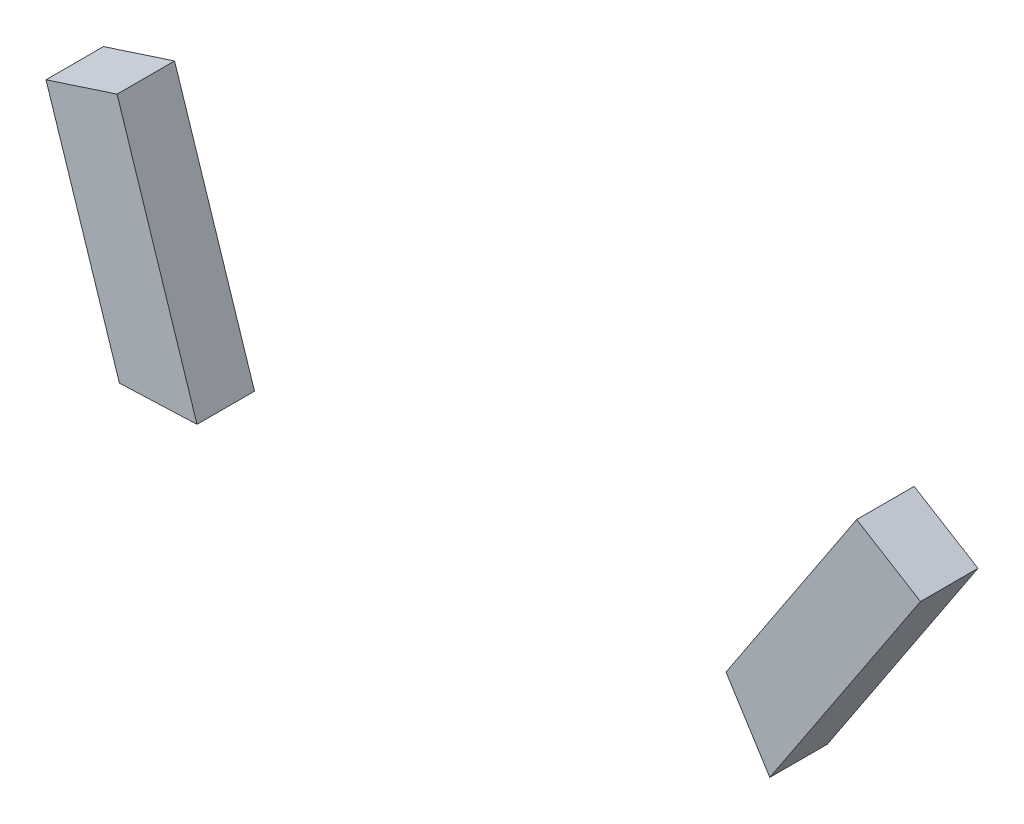
SolidWorks part; units mm, degrees
ref_plane "Front Plane" through (0, 0, 0) normal (0, 0, 1) x (1, 0, 0)
ref_plane "Top Plane" through (0, 0, 0) normal (0, 1, 0) x (1, 0, 0)
ref_plane "Right Plane" through (0, 0, 0) normal (1, 0, 0) x (0, 0, -1)
sketch "Sketch1" plane through (0, 0, 0) normal (0, 0, 1) x (1, 0, 0)
  line L0 (0, -21.2809) -> (0, 20.8576) construction
  line L1 (-23.4901, 0) -> (24.9244, 0) construction
  line L2 (0, 0) -> (5.5969, 9.6942) construction
  line L3 (0, 0) -> (-5.6466, 9.7801) construction
  line L4 (2.05, 3.5507) -> (-1.6508, 5.6874) construction
  line L5 (-2.05, 3.5507) -> (1.6508, 5.6874) construction
  line L6 (0.8318, 0.175) -> (2.7945, 0.175)
  line L7 (0.8318, -0.175) -> (2.7945, -0.175)
  line L8 (-0.175, 0.8318) -> (-0.175, 2.7945)
  line L9 (0.175, 0.8318) -> (0.175, 2.7945)
  line L10 (0.175, -0.8318) -> (0.175, -2.7945)
  line L11 (-0.175, -0.8318) -> (-0.175, -2.7945)
  line L12 (-0.8318, -0.175) -> (-2.7945, -0.175)
  line L13 (-0.8318, 0.175) -> (-2.7945, 0.175)
  line L14 (0, 0) -> (6.6911, 7.6973) construction
  line L15 (0, 0) -> (-6.6911, 7.6973) construction
  line L16 (0, 4.7343) -> (6.5895, 2.1386) construction
  line L17 (2.6898, 3.0943) -> (2.2024, 3.8667)
  line L18 (0, 0) -> (2.5071, 3.384) construction
  line L19 (2.5071, 3.384) -> (2.4713, 3.3358)
  line L20 (2.6898, 3.0943) -> (1.7172, 2.6408)
  line L21 (3.6667, 2.0717) -> (3.6145, 2.0422)
  line L22 (3.7159, 1.7327) -> (3.5847, 2.6366)
  line L23 (3.7159, 1.7327) -> (2.6429, 1.714)
  line L24 (4.1923, 0.4012) -> (4.1326, 0.3955)
  line L25 (4.0994, 0.0716) -> (4.3472, 0.9506)
  line L26 (4.0994, 0.0716) -> (3.1115, 0.4909)
  line L27 (3.9931, -1.3387) -> (3.9362, -1.3196)
  line L28 (3.7741, -1.602) -> (4.3581, -0.8998)
  line L29 (3.7741, -1.602) -> (3.0422, -0.8171)
  line L30 (3.1034, -2.847) -> (3.0592, -2.8065)
  line L31 (2.7962, -2.9986) -> (3.6153, -2.5945)
  line L32 (2.7962, -2.9986) -> (2.4468, -1.9838)
  line L33 (1.6771, -3.8632) -> (1.6532, -3.8081)
  line L34 (1.3348, -3.8766) -> (2.2475, -3.8407)
  line L35 (1.3348, -3.8766) -> (1.4284, -2.8075)
  line L36 (-0.0392, -4.2113) -> (-0.0387, -4.1513)
  line L37 (-0.3573, -4.0844) -> (0.491, -4.4228)
  line L38 (-0.3573, -4.0844) -> (0.1629, -3.1458)
  line L39 (-1.7487, -3.8313) -> (-1.7238, -3.7767)
  line L40 (-1.9877, -3.5859) -> (-1.3504, -4.2401)
  line L41 (-1.9877, -3.5859) -> (-1.1306, -2.9401)
  line L42 (-3.1558, -2.7888) -> (-3.1109, -2.749)
  line L43 (-3.2744, -2.4674) -> (-2.9582, -3.3243)
  line L44 (-3.2744, -2.4674) -> (-2.2287, -2.226)
  line L45 (-4.0173, -1.2641) -> (-3.9601, -1.2461)
  line L46 (-3.9949, -0.9223) -> (-4.0546, -1.8337)
  line L47 (-3.9949, -0.9223) -> (-2.9415, -1.1271)
  line L48 (-4.1841, 0.4792) -> (-4.1245, 0.4724)
  line L49 (-4.0247, 0.7823) -> (-4.4499, -0.026)
  line L50 (-4.0247, 0.7823) -> (-3.1456, 0.1668)
  line L51 (-3.6275, 2.1396) -> (-3.5758, 2.1091)
  line L52 (-3.3585, 2.3517) -> (-4.0757, 1.7862)
  line L53 (-3.3585, 2.3517) -> (-2.8058, 1.4318)
  line L54 (-2.4436, 3.4301) -> (-2.4088, 3.3812)
  line L55 (-2.1117, 3.5144) -> (-2.9969, 3.2895)
  line L56 (-2.1117, 3.5144) -> (-1.9809, 2.4492)
  line L57 (-0.8372, 4.1274) -> (-0.8253, 4.0686)
  line L58 (-0.4997, 4.0694) -> (-1.3998, 4.2241)
  line L59 (-0.4997, 4.0694) -> (-0.8134, 3.0432)
  line L60 (0.9139, 4.1111) -> (0.9009, 4.0525)
  line L61 (1.1987, 3.9208) -> (0.4393, 4.4282)
  line L62 (1.1987, 3.9208) -> (0.4947, 3.1109)
  line L63 (0, 4.7343) -> (-2.5531, 3.1697) construction
  line L64 (-2.05, 3.5507) -> (-2.4328, 4.7289) construction
  line L65 (-2.0183, 3.4974) -> (-2.5292, 5.0699)
  line L66 (2.5071, 4.3424) -> (3.1715, 5.3462) construction
  line L67 (2.2024, 3.8667) -> (3.1115, 5.2402)
  line L68 (2.5071, 3.384) -> (3.5557, 4.9683)
  line L69 (3.5557, 4.9683) -> (3.1115, 5.2402)
  line L70 (-2.5292, 5.0699) -> (-2.0347, 5.2306)
  line L71 (-2.0347, 5.2306) -> (-1.4785, 3.5187)
  line L72 (-2.1117, 3.5144) -> (-1.2626, 3.7301) construction
  line L73 (-2.0183, 3.4974) -> (-1.4785, 3.5187)
  line L74 (0, 4.7343) -> (-0.7323, 13.1045) construction
  line L75 (3.1336, 5.4612) -> (3.7485, 5.0848)
  line L76 (3.7797, 4.9444) -> (3.2146, 4.0906)
  line L77 (2.998, 5.4311) -> (2.9748, 5.396)
  line L78 (0.067, 6.2631) -> (0.1001, 5.8849)
  line L79 (3.2146, 4.0906) -> (2.93, 3.9142)
  line L80 (2.93, 3.9142) -> (2.88, 3.9474)
  line L81 (-2.6861, 5.2292) -> (-2.0014, 5.4517)
  line L82 (-1.8754, 5.3875) -> (-1.7926, 5.1326)
  line L83 (-2.7504, 5.1032) -> (-2.4797, 4.2702)
  line L84 (-2.4797, 4.2702) -> (-2.2599, 4.0467)
  line L85 (-2.2599, 4.0467) -> (-2.2028, 4.0652)
  line L86 (-0.3315, 6.2283) -> (-0.2984, 5.85)
  line L87 (0.067, 6.2631) -> (-0.31, 10.5723)
  line L88 (-0.3315, 6.2283) -> (-0.7085, 10.5374)
  line L89 (0, 4.7343) -> (-1.8171, 12.9313) construction
  line L90 (0, 13.1343) -> (-1.0909, 9.5661) construction
  line L91 (-0.2672, 11.2304) -> (-0.2957, 11.5563)
  line L92 (-0.8649, 11.1781) -> (-0.8934, 11.504)
  line L93 (-0.8649, 11.1781) -> (-0.2672, 11.2304)
  line L94 (-0.5939, 10.5474) -> (-0.4246, 10.5622)
  line L95 (-0.4246, 10.5622) -> (-0.5425, 11.9099)
  line L96 (-0.5425, 11.9099) -> (-0.64, 12.0491)
  line L97 (-0.5939, 10.5474) -> (-0.7118, 11.895)
  line L98 (-0.7118, 11.895) -> (-0.64, 12.0491)
  line L99 (-0.3654, 10.9187) -> (-0.3218, 10.4206)
  line L100 (-0.3218, 10.4206) -> (-0.6705, 10.3901)
  line L101 (-0.6705, 10.3901) -> (-0.7141, 10.8882)
  line L102 (-0.7141, 10.8882) -> (-0.3654, 10.9187)
  circle A0 centre (0, 0) radius 4.1
  circle A1 centre (0, 4.7343) radius 0.25
  circle A2 centre (0, 0) radius 0.35
  arc A3 (-0.175, 0.8318) -> (-0.8318, 0.175) centre (0, 0) ccw
  arc A4 (-0.175, 2.7945) -> (-2.7945, 0.175) centre (0, 0) ccw
  arc A5 (0.6577, 3.0806) -> (0.4947, 3.1109) centre (0, 0) ccw
  arc A6 (-0.8318, -0.175) -> (-0.175, -0.8318) centre (0, 0) ccw
  arc A7 (0.8318, 0.175) -> (0.175, 0.8318) centre (0, 0) ccw
  arc A8 (0.175, -0.8318) -> (0.8318, -0.175) centre (0, 0) ccw
  arc A9 (-2.7945, -0.175) -> (-0.175, -2.7945) centre (0, 0) ccw
  arc A10 (2.7945, 0.175) -> (0.175, 2.7945) centre (0, 0) ccw
  arc A11 (0.175, -2.7945) -> (2.7945, -0.175) centre (0, 0) ccw
  arc A12 (2.05, 3.5507) -> (1.8799, 6.1728) centre (0, 4.7343) ccw
  circle A13 centre (0, 0) radius 4.2115
  arc A14 (2.4713, 3.3358) -> (2.4182, 3.0865) centre (2.388, 3.2233) cw
  arc A15 (0.6577, 3.0806) -> (2.4182, 3.0865) centre (1.5242, 7.1391) ccw
  arc A16 (1.8538, 2.5467) -> (3.4645, 1.8361) centre (4.2961, 5.902) ccw
  arc A17 (2.7628, 3.1783) -> (2.7631, 3.1784) centre (1.5242, 7.1391) ccw
  arc A18 (3.6145, 2.0422) -> (3.4645, 1.8361) centre (3.4926, 1.9733) cw
  arc A19 (2.7294, 1.5725) -> (3.9118, 0.2683) centre (6.3253, 3.6443) ccw
  arc A20 (4.1326, 0.3955) -> (3.9118, 0.2683) centre (3.9932, 0.3821) cw
  arc A21 (3.133, 0.3264) -> (3.6827, -1.346) centre (7.2607, 0.7565) ccw
  arc A22 (3.9362, -1.3196) -> (3.6827, -1.346) centre (3.8034, -1.2751) cw
  arc A23 (2.995, -0.9761) -> (2.8169, -2.7275) centre (6.9407, -2.2621) ccw
  arc A24 (3.0592, -2.8065) -> (2.8169, -2.7275) centre (2.956, -2.7118) cw
  arc A25 (2.339, -2.1099) -> (1.4639, -3.6375) centre (5.4206, -4.8895) ccw
  arc A26 (1.6532, -3.8081) -> (1.4639, -3.6375) centre (1.5974, -3.6797) cw
  arc A27 (1.2786, -2.8788) -> (-0.1421, -3.9184) centre (2.9632, -6.6715) ccw
  arc A28 (-0.0387, -4.1513) -> (-0.1421, -3.9184) centre (-0.0374, -4.0113) cw
  arc A29 (-0.0028, -3.15) -> (-1.7236, -3.5219) centre (-0.0066, -7.3) ccw
  arc A30 (-1.7238, -3.7767) -> (-1.7236, -3.5219) centre (-1.6657, -3.6493) cw
  arc A31 (-1.2838, -2.8765) -> (-3.007, -2.5163) centre (-2.9752, -6.6662) ccw
  arc A32 (-3.1109, -2.749) -> (-3.007, -2.5163) centre (-3.006, -2.6563) cw
  arc A33 (-2.3428, -2.1057) -> (-3.7706, -1.0757) centre (-5.4293, -4.8798) ccw
  arc A34 (-3.9601, -1.2461) -> (-3.7706, -1.0757) centre (-3.8265, -1.204) cw
  arc A35 (-2.9967, -0.9707) -> (-3.8821, 0.5509) centre (-6.9447, -2.2496) ccw
  arc A36 (-4.1245, 0.4724) -> (-3.8821, 0.5509) centre (-3.9854, 0.4564) cw
  arc A37 (-3.1324, 0.3321) -> (-3.3224, 2.0823) centre (-7.2593, 0.7696) ccw
  arc A38 (-3.5758, 2.1091) -> (-3.3224, 2.0823) centre (-3.4552, 2.038) cw
  arc A39 (-2.7266, 1.5775) -> (-2.1882, 3.2536) centre (-6.3187, 3.6557) ccw
  arc A40 (-2.4088, 3.3812) -> (-2.1882, 3.2536) centre (-2.3276, 3.2672) cw
  arc A41 (-1.8492, 2.5501) -> (-0.6757, 3.8623) centre (-4.2855, 5.9097) ccw
  arc A42 (-0.8253, 4.0686) -> (-0.6757, 3.8623) centre (-0.7975, 3.9314) cw
  arc A43 (-0.6522, 3.0818) -> (0.9537, 3.8033) centre (-1.5113, 7.1418) ccw
  arc A44 (0.9009, 4.0525) -> (0.9537, 3.8033) centre (0.8705, 3.9159) cw
  arc A45 (2.0666, 2.3773) -> (1.575, 2.728) centre (0, 0) ccw
  arc A46 (2.7294, 1.5725) -> (2.6429, 1.714) centre (0, 0) ccw
  arc A47 (3.133, 0.3264) -> (3.1115, 0.4909) centre (0, 0) ccw
  arc A48 (2.995, -0.9761) -> (3.0422, -0.8171) centre (0, 0) ccw
  arc A49 (2.339, -2.1099) -> (2.4468, -1.9838) centre (0, 0) ccw
  arc A50 (-0.6522, 3.0818) -> (-0.8134, 3.0432) centre (0, 0) ccw
  arc A51 (-1.575, 2.728) -> (-2.0666, 2.3773) centre (0, 0) ccw
  arc A52 (-2.7266, 1.5775) -> (-2.8058, 1.4318) centre (0, 0) ccw
  arc A53 (-3.1324, 0.3321) -> (-3.1456, 0.1668) centre (0, 0) ccw
  arc A54 (-2.9967, -0.9707) -> (-2.9415, -1.1271) centre (0, 0) ccw
  arc A55 (-2.3428, -2.1057) -> (-2.2287, -2.226) centre (0, 0) ccw
  arc A56 (-1.2838, -2.8765) -> (-1.1306, -2.9401) centre (0, 0) ccw
  arc A57 (-0.0028, -3.15) -> (0.1629, -3.1458) centre (0, 0) ccw
  arc A58 (1.2786, -2.8788) -> (1.4284, -2.8075) centre (0, 0) ccw
  arc A59 (-2.05, 3.5507) -> (-0.5036, 2.4213) centre (0, 4.7343) ccw
  arc A60 (1.0177, 5.1638) -> (2.0583, 5.0774) centre (1.3569, 2.9395) cw
  arc A61 (0.2412, 4.4152) -> (2.5336, 4.367) centre (1.3569, 2.9395) cw
  arc A62 (-0.2238, 4.4028) -> (-1.7102, 4.232) centre (-0.8673, 3.4497) ccw
  arc A63 (3.7485, 5.0848) -> (3.7797, 4.9444) centre (3.6963, 4.9996) cw
  arc A64 (2.998, 5.4311) -> (3.1336, 5.4612) centre (3.0814, 5.3759) cw
  arc A65 (-0.2238, 4.4028) -> (0.2412, 4.4152) centre (0, 4.7343) ccw
  arc A66 (2.9748, 5.396) -> (2.0583, 5.0774) centre (2.3077, 5.8375) cw
  arc A67 (1.0177, 5.1638) -> (0.1001, 5.8849) centre (0.8971, 5.9546) cw
  arc A68 (-1.8754, 5.3875) -> (-2.0014, 5.4517) centre (-1.9705, 5.3566) ccw
  arc A69 (-2.7504, 5.1032) -> (-2.6861, 5.2292) centre (-2.6552, 5.1341) cw
  arc A70 (-0.2984, 5.85) -> (-0.754, 5.1723) centre (-0.9459, 5.7934) cw
  arc A71 (-1.7926, 5.1326) -> (-1.5095, 5.0037) centre (-1.5211, 5.3535) ccw
  arc A72 (-0.31, 10.5723) -> (-0.0079, 11.1276) centre (0.2577, 10.6233) cw
  arc A73 (-0.0652, 5.4791) -> (0, 5.5041) centre (-2.8729, 12.8867) ccw
  arc A74 (-1.5095, 5.0037) -> (-0.754, 5.1723) centre (-2.8729, 12.8867) ccw
  arc A75 (-0.0079, 11.1276) -> (0.0594, 11.5321) centre (0.4209, 11.2641) cw
  arc A76 (0.0594, 11.5321) -> (0.2329, 11.9395) centre (-0.7039, 12.0977) ccw
  arc A77 (-0.3152, 11.3278) -> (-0.8812, 11.5261) centre (-0.5952, 11.4355) ccw
  circle A78 centre (0, 13.1343) radius 1.2
  circle A79 centre (0, 13.1343) radius 2
  arc A80 (-0.7085, 10.5374) -> (-1.1024, 11.0318) centre (-1.2764, 10.489) ccw
  arc A81 (-1.1024, 11.0318) -> (-1.2389, 11.4185) centre (-1.5484, 11.0918) ccw
  arc A82 (-1.2389, 11.4185) -> (-1.4805, 11.7896) centre (-0.5855, 12.1081) cw
  arc A83 (-1.4805, 11.7896) -> (-0.8934, 11.504) centre (-0.6802, 12.6886) ccw
  arc A84 (0.2329, 11.9395) -> (-0.2957, 11.5563) centre (-0.7114, 12.6858) cw
  circle A85 centre (0, 13.1343) radius 1.8
  arc A86 (-0.8715, 11.5024) -> (-0.3375, 11.3153) centre (0, 13.1343) ccw
  arc A87 (-0.3375, 11.3153) -> (-0.3152, 11.3278) centre (-0.3338, 11.335) ccw
  circle A88 centre (0, 13.1343) radius 1.85 construction
  arc A89 (-0.8789, 11.3381) -> (-0.8787, 11.3377) centre (-0.5952, 11.4355) ccw
  arc A90 (-0.8715, 11.5024) -> (-0.8812, 11.5261) centre (-0.8621, 11.5201) cw
  circle A91 centre (0, 13.1343) radius 0.4
  point P36 (0, 0)
  point P40 (2.5071, 3.384)
  point P180 (0, 0)
  point P182 (-2.0183, 3.4974)
  point P245 (0, 13.1343)
  point P252 (-0.5661, 11.2043)
  point P268 (-0.5661, 11.2043)
  point P273 (-0.5092, 10.5548)
  point P276 (1.85, 13.1343)
  dimension "D1" = 8.2
  dimension "D4" = 0.5
  dimension "D5" = 0.7
  dimension "D6" = 1.7
  dimension "D7" = 5.6
  dimension "D8" = 6.3
  dimension "D17" = 0.14
  dimension "D18" = 8.3
  dimension "D28" = 0.4
  dimension "D29" = 1.85
  dimension "D31" = 1.15
  dimension "D34" = 2.25
  dimension "D37" = 0.1
  dimension "D39" = 0.1
  dimension "D40" = 0.8
  dimension "D41" = 0.8
  dimension "D46" = 0.1
  dimension "D48" = 0.1
  dimension "D52" = 0.35
  dimension "D53" = 0.65
  dimension "D54" = 0.2
  dimension "D55" = 0.95
  dimension "D56" = 0.45
  dimension "D57" = 0.57
  dimension "D58" = 0.2375
  dimension "D61" = 0.6
  dimension "D62" = 2.4
  dimension "D64" = 4
  dimension "D65" = 3.6
  dimension "D70" = 0.05
  dimension "D71" = 0.02
  dimension "D76" = 0.8
  dimension "D2" = 60
  dimension "D3" = 30
  dimension "D9" = 0.35
  dimension "D11" = 11
  dimension "D12" = 8.5
  dimension "D13" = 0.9133
  dimension "D14" = 0.3425
  dimension "D15" = 0.06
  dimension "D16" = 24
  dimension "D20" = 1.5
  dimension "D21" = 12
  dimension "D22" = 1.8
  dimension "D23" = 3.5
  dimension "D24" = 1.6471
  dimension "D25" = 1.9
  dimension "D26" = 0.52
  dimension "D27" = 12
  dimension "D30" = 0.6
  dimension "D32" = 0.75
  dimension "D33" = 5
  dimension "D35" = 0.2
  dimension "D36" = 0.2
  dimension "D38" = 0.2
  dimension "D42" = 0.06
  dimension "D43" = 1
  dimension "D44" = 0.2
  dimension "D45" = 0.2
  dimension "D47" = 0.2
  dimension "D49" = 0.9
  dimension "D50" = 0.6
  dimension "D51" = 0.06
  dimension "D59" = 1.93
  dimension "D60" = 8.4
  dimension "D63" = 17
  dimension "D66" = 0.17
  dimension "D67" = 1.5
  dimension "D68" = 30
  dimension "D69" = 0.6
  dimension "D72" = 0.35
  dimension "D73" = 0.175
  dimension "D74" = 0.5
  dimension "D75" = 0.15
  dimension "D10" = 4
  dimension "D19" = 15
extrude "Boss-Extrude1" add sketch "Sketch1" along normal blind 0.4 contours L68 L69 L67 L17 | A13 L71 L70 L65 | L71 A13 L65 A0 | L71 A0 L65 L73
equation "\"D14@Sketch1\"=\"D13@Sketch1\"*3/8"
